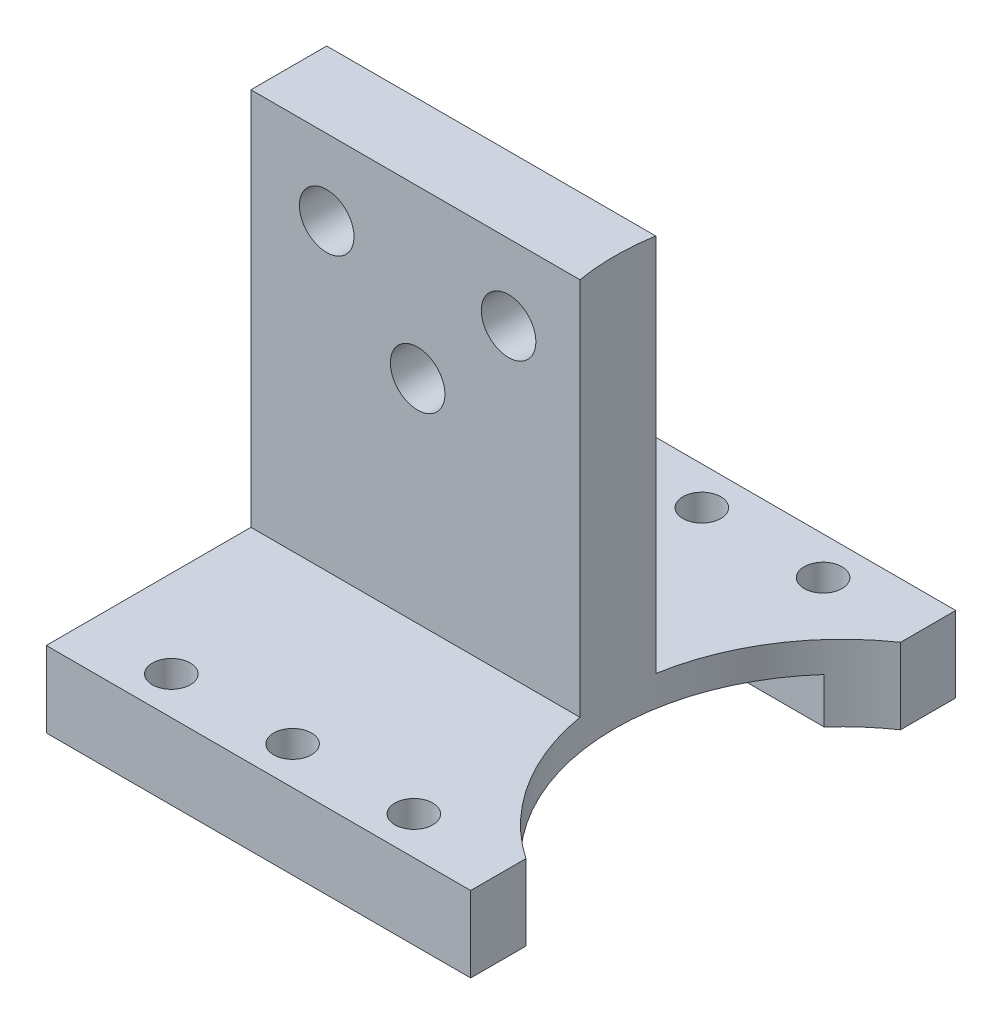
SolidWorks part; units mm, degrees
ref_plane "Płaszczyzna przednia" through (0, 0, 0) normal (0, 0, 1) x (1, 0, 0)
ref_plane "Płaszczyzna górna" through (0, 0, 0) normal (0, 1, 0) x (1, 0, 0)
ref_plane "Płaszczyzna prawa" through (0, 0, 0) normal (1, 0, 0) x (0, 0, -1)
sketch "Szkic1" plane through (0, 0, 0) normal (0, 1, 0) x (1, 0, 0)
  line L1 (-10, 10) -> (10, 10)
  line L2 (-10, 10) -> (-10, -10)
  line L3 (-10, -10) -> (10, -10)
  line L4 (10, 10) -> (10, -10)
  line L5 (-10, 10) -> (10, -10) construction
  line L6 (-10, -10) -> (10, 10) construction
  point P0 (0, 0)
  dimension "D1" = 20
  dimension "D2" = 20
extrude "Dodanie-wyciągnięcie1" add sketch "Szkic1" along normal blind 2
sketch "Szkic3" plane through (0, 2, 0) normal (0, 1, 0) x (1, 0, 0)
  line L0 (-8.25, 13.5) -> (7.75, 13.5) construction
  line L1 (-8.25, -13.5) -> (7.75, -13.5) construction
  line L2 (-1.0256, 0) -> (-7.5044, 0) construction
  line L3 (-10, 10) -> (-10, -10) construction
  line L4 (-14, -16) -> (10, -16)
  line L5 (-14, -16) -> (-14, 16)
  line L6 (-14, 16) -> (10, 16)
  line L7 (10, -16) -> (10, 16)
  line L8 (-14, -16) -> (10, 16) construction
  line L9 (-14, 16) -> (10, -16) construction
  line L10 (10, 10) -> (-10, 10) construction
  line L12 (10, -10) -> (10, 10) construction
  line L14 (10, 10) -> (-10, 10)
  line L15 (10, 10) -> (10, -10)
  line L16 (10, -10) -> (-10, -10)
  line L17 (-10, 10) -> (-10, -10)
  circle A6 centre (7.75, -13.5) radius 1.25
  circle A7 centre (-0.25, -13.5) radius 1.25
  circle A8 centre (-8.25, -13.5) radius 1.25
  circle A9 centre (7.75, 13.5) radius 1.25
  circle A10 centre (-0.25, 13.5) radius 1.25
  circle A11 centre (-8.25, 13.5) radius 1.25
  point P5 (-2, 0)
  line M2 (10, 10) -> (-10, 10)
  line M3 (-10, 10) -> (-10, -10)
  line M4 (-10, -10) -> (10, -10)
  dimension "D1" = 2.5
  dimension "D2" = 8
  dimension "D3" = 8
  dimension "D4" = 27
  dimension "D5" = 4
  dimension "D6" = 6
extrude "Dodanie-wyciągnięcie2" add sketch "Szkic3" against normal blind 5 contours L4 L7 L6 L5 A11 A10 A9 A8 A7 A6 M4 M3 M2
sketch "Szkic4" plane through (0, 2, 0) normal (0, 1, 0) x (1, 0, 0)
  line L0 (-14, 0) -> (10, 0) construction
  line L1 (-14, -16) -> (-14, 16) construction
  line L2 (10, -16) -> (10, 16) construction
  line L4 (10, 2.5) -> (-14, 2.5)
  line L5 (10, 2.5) -> (10, -2.5)
  line L6 (10, -2.5) -> (-14, -2.5)
  line L7 (-14, 2.5) -> (-14, -2.5)
  line L8 (10, 2.5) -> (-14, -2.5) construction
  line L9 (10, -2.5) -> (-14, 2.5) construction
  point P6 (-2, 0)
  point P11 (10, -4.1963)
  dimension "D1" = 5
extrude "Dodanie-wyciągnięcie3" add sketch "Szkic4" along normal blind 25
sketch "Szkic5" plane through (10, 0, 0) normal (1, 0, 0) x (0, 0, -1)
  line L12 (-10, 0) -> (10, 0)
  line L13 (10, 0) -> (10, -3)
  line L14 (10, -3) -> (16, -3)
  line L15 (16, -3) -> (16, 2)
  line L16 (16, 2) -> (2.5, 2)
  line L17 (2.5, 2) -> (2.5, 27)
  line L18 (2.5, 27) -> (-2.5, 27)
  line L19 (-2.5, 27) -> (-2.5, 2)
  line L20 (-2.5, 2) -> (-16, 2)
  line L21 (-16, 2) -> (-16, -3)
  line L22 (-16, -3) -> (-10, -3)
  line L23 (-10, -3) -> (-10, 0)
  line L24 (-10, 0) -> (10, 0)
  line L25 (10, 0) -> (10, -3)
  line L26 (10, -3) -> (16, -3)
  line L27 (16, -3) -> (16, 2)
  line L28 (16, 2) -> (2.5, 2)
  line L29 (2.5, 2) -> (2.5, 27)
  line L30 (2.5, 27) -> (-2.5, 27)
  line L31 (-2.5, 27) -> (-2.5, 2)
  line L32 (-2.5, 2) -> (-16, 2)
  line L33 (-16, 2) -> (-16, -3)
  line L34 (-16, -3) -> (-10, -3)
  line L35 (-10, -3) -> (-10, 0)
  dimension "D1" = 0
extrude "Dodanie-wyciągnięcie4" add sketch "Szkic5" along normal blind 4
sketch "Szkic6" plane through (0, 27, 0) normal (0, 1, 0) x (1, 0, 0)
  line L0 (0, 0) -> (22.5, 0) construction
  circle A0 centre (22.5, 0) radius 15
  dimension "D1" = 30
extrude "Wytnij-wyciągnięcie1" cut sketch "Szkic6" against normal blind 34 contours A0
sketch "Szkic10" plane through (0, 0, 2.5) normal (0, 0, 1) x (1, 0, 0)
  line L0 (-9, 22) -> (3, 22) construction
  line L4 (-3, 22) -> (-3, 16) construction
  line L7 (-14, 27) -> (-14, 2) construction
  line L8 (-14, 27) -> (7.7098, 27) construction
  point P0 (3, 22)
  point P2 (-9, 22)
  point P4 (-3, 16)
  point P20 (-3.5923, 16.4778)
  dimension "D1" = 12
  dimension "D2" = 6
  dimension "D3" = 5
  dimension "D4" = 5
hole_wizard "Otwór pod śrubę M31" positions "Szkic10" profile "Szkic8" hole size "M3" standard "DIN"
sketch "Szkic8" plane through (3, 22, 2.5) normal (1, 0, 0) x (0, -1, 0)
  line L0 (0, 0) -> (0, 24)
  line L1 (0, 24) -> (1.8, 24)
  line L2 (1.8, 24) -> (1.8, 0)
  line L5 (1.8, 0) -> (0, 0)
  line L10 (0, 24) -> (-1.8, 24) construction
  line L11 (0, -6.35) -> (0, 107.95) construction
  dimension "Średnica otworu" = 3.6
  dimension "Głębokość otworu" = 24
  dimension "Kąt wiertła" = 180
